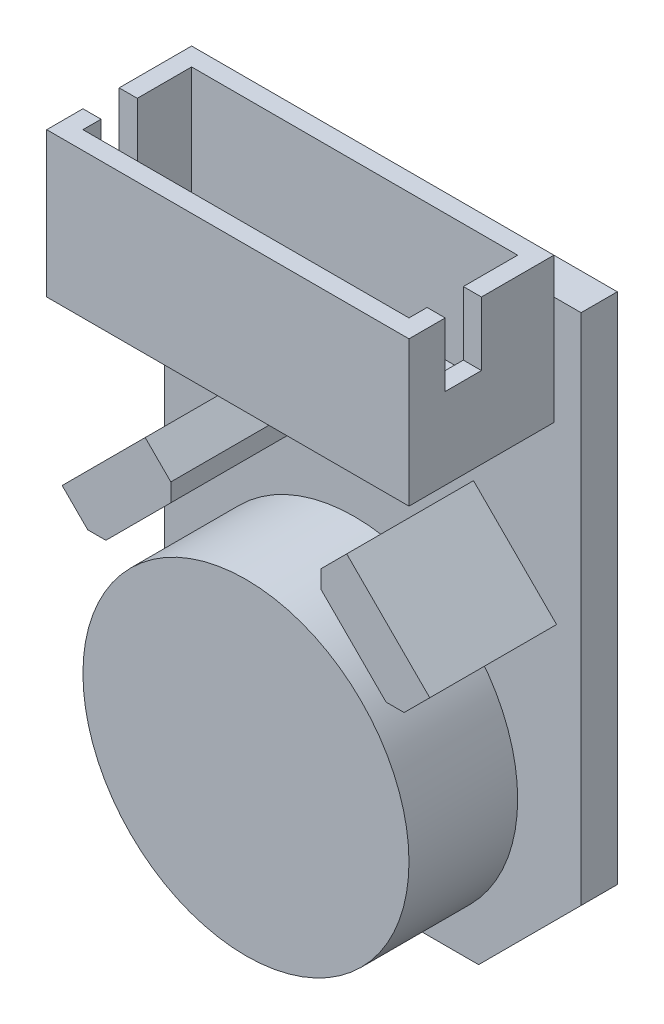
SolidWorks part; units mm, degrees
ref_plane "Alzado" through (0, 0, 0) normal (0, 0, 1) x (1, 0, 0)
ref_plane "Planta" through (0, 0, 0) normal (0, 1, 0) x (1, 0, 0)
ref_plane "Vista lateral" through (0, 0, 0) normal (1, 0, 0) x (0, 0, -1)
sketch "Croquis1" plane through (0, 0, 0) normal (0, 0, 1) x (1, 0, 0)
  line L0 (-5.75, -5.6716) -> (-2.9216, -8.5)
  line L1 (-2.9216, -8.5) -> (2.9216, -8.5)
  line L2 (-5.75, -5.6716) -> (-5.75, 8.5)
  line L3 (-5.75, 8.5) -> (5.75, 8.5)
  line L4 (5.75, -5.6716) -> (5.75, 8.5)
  line L5 (-5.75, -8.5) -> (5.75, 8.5) construction
  line L6 (-5.75, 8.5) -> (5.75, -8.5) construction
  line L7 (2.9216, -8.5) -> (5.75, -5.6716)
  point P0 (0, 0)
  dimension "D1" = 11.5
  dimension "D2" = 17
  dimension "D3" = 4
  dimension "D4" = 45
  dimension "D6" = 45
  dimension "D7" = 4
extrude "Saliente-Extruir1" add sketch "Croquis1" along normal blind 1
sketch "Croquis2" plane through (0, 0, 1) normal (0, 0, 1) x (1, 0, 0)
  line L0 (-5.75, 8.5) -> (-5.75, 3)
  line L1 (-5.75, 8.5) -> (-5.75, -5.6716) construction
  line L2 (-5.75, 3) -> (-5.75, 0)
  line L3 (-5.75, 3) -> (13.5124, 3)
  line L4 (-5.75, 0) -> (15.2049, 0)
  line L5 (-2.7809, 3) -> (-5.0738, 0.7071)
  line L6 (-5.0738, 0.7071) -> (-4.3667, 0)
  line L7 (-4.3667, 0) -> (-3.8667, 0)
  line L8 (-3.8667, 0) -> (-2.0738, 1.7929)
  line L9 (-2.0738, 1.7929) -> (-2.0738, 2.2929)
  line L10 (-2.0738, 2.2929) -> (-2.7809, 3)
  line L11 (0, 0) -> (0, 17.7072) construction
  line L12 (2.0738, 1.7929) -> (2.0738, 2.2929)
  line L13 (3.8667, 0) -> (2.0738, 1.7929)
  line L14 (4.3667, 0) -> (3.8667, 0)
  line L15 (5.0738, 0.7071) -> (4.3667, 0)
  line L16 (2.7809, 3) -> (5.0738, 0.7071)
  line L17 (2.0738, 2.2929) -> (2.7809, 3)
  dimension "D1" = 5.5
  dimension "D2" = 3
  dimension "D3" = 1
  dimension "D4" = 1
  dimension "D5" = 0.5
  dimension "D6" = 0.5
extrude "Saliente-Extruir2" add sketch "Croquis2" along normal blind 3.5 contours L10 L5 L6 L7 L8 L9 | L12 L17 L16 L15 L14 L13
sketch "Croquis3" plane through (0, 0, 0) normal (0, 0, 1) x (1, 0, 0)
  line L1 (-2.9216, -8.5) -> (2.9216, -8.5) construction
  circle A0 centre (0, -3.5) radius 0.25
  dimension "D2" = 0.5
  dimension "D1" = 5
extrude "Saliente-Extruir3" add sketch "Croquis3" along normal blind 4.5
sketch "Croquis4" plane through (0, 0, 4.5) normal (0, 0, 1) x (1, 0, 0)
  circle A0 centre (0, -3.5) radius 4.5
  dimension "D1" = 9
extrude "Saliente-Extruir4" add sketch "Croquis4" against normal blind 3
sketch "Croquis5" plane through (0, 0, 1) normal (0, 0, 1) x (1, 0, 0)
  line L0 (5.75, 8.5) -> (-5.75, 8.5) construction
  line L1 (5, 5.5) -> (-5, 5.5)
  line L2 (5, 5.5) -> (5, 9.5)
  line L3 (5, 9.5) -> (-5, 9.5)
  line L4 (-5, 5.5) -> (-5, 9.5)
  line L5 (5, 5.5) -> (-5, 9.5) construction
  line L6 (5, 9.5) -> (-5, 5.5) construction
  point P0 (0, 7.5)
  point P7 (0, 0)
  point P8 (0, 8.5)
  dimension "D1" = 10
  dimension "D2" = 4
  dimension "D3" = 1
extrude "Saliente-Extruir5" add sketch "Croquis5" along normal blind 4
sketch "Croquis6" plane through (0, 9.5, 0) normal (0, 1, 0) x (1, 0, 0)
  line L0 (-5, -5) -> (-5, -1) construction
  line L1 (4.5, -4.5) -> (-4.5, -4.5)
  line L2 (4.5, -4.5) -> (4.5, -1.5)
  line L3 (4.5, -1.5) -> (-4.5, -1.5)
  line L4 (-4.5, -4.5) -> (-4.5, -1.5)
  line L5 (4.5, -4.5) -> (-4.5, -1.5) construction
  line L6 (4.5, -1.5) -> (-4.5, -4.5) construction
  line L7 (5, -5) -> (-5, -5) construction
  line L8 (5, -1) -> (-5, -1) construction
  line L9 (5, -5) -> (5, -1) construction
  point P0 (0, -3)
  dimension "D1" = 0.5
  dimension "D2" = 0.5
  dimension "D3" = 0.5
  dimension "D4" = 0.5
extrude "Cortar-Extruir1" cut sketch "Croquis6" against normal blind 3.5
sketch "Croquis7" plane through (5, 0, 0) normal (1, 0, 0) x (0, 0, -1)
  line L0 (-5, 5.5) -> (-5, 9.5) construction
  line L1 (-4, 7.7411) -> (-3, 7.7411)
  line L2 (-4, 7.7411) -> (-4, 9.7411)
  line L3 (-4, 9.7411) -> (-3, 9.7411)
  line L4 (-3, 7.7411) -> (-3, 9.7411)
  line L5 (-4, 7.7411) -> (-3, 9.7411) construction
  line L6 (-4, 9.7411) -> (-3, 7.7411) construction
  point P0 (-3.5, 8.7411)
  dimension "D1" = 2
  dimension "D2" = 1
  dimension "D3" = 1
extrude "Cortar-Extruir2" cut sketch "Croquis7" against normal through all
